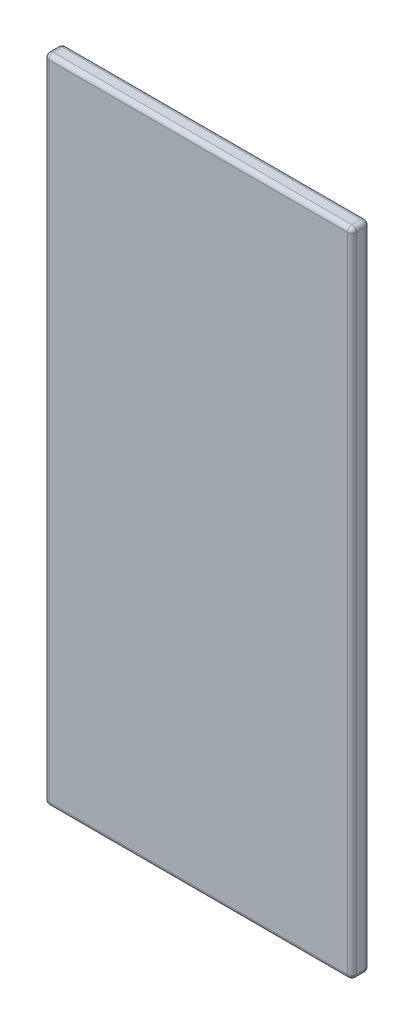
SolidWorks part; units mm, degrees
ref_plane "Front Plane" through (0, 0, 0) normal (0, 0, 1) x (1, 0, 0)
ref_plane "Top Plane" through (0, 0, 0) normal (0, 1, 0) x (1, 0, 0)
ref_plane "Right Plane" through (0, 0, 0) normal (1, 0, 0) x (0, 0, -1)
sketch "Sketch1" plane through (0, 0, 0) normal (0, 0, 1) x (1, 0, 0)
  line L1 (-17.35, -36.75) -> (17.35, -36.75)
  line L2 (-17.35, -36.75) -> (-17.35, 36.75)
  line L3 (-17.35, 36.75) -> (17.35, 36.75)
  line L4 (17.35, -36.75) -> (17.35, 36.75)
  line L5 (-17.35, -36.75) -> (17.35, 36.75) construction
  line L6 (-17.35, 36.75) -> (17.35, -36.75) construction
  point P0 (0, 0)
  dimension "D1" = 34.7
  dimension "D2" = 73.5
extrude "Boss-Extrude1" add sketch "Sketch1" along normal blind 2
fillet "Fillet1" radius 0.5 12 edges at (0, -36.75, 2) (0, -36.75, 0) (-17.35, 0, 2) (-17.35, -36.75, 1) (-17.35, 0, 0) (0, 36.75, 2) (-17.35, 36.75, 1) (0, 36.75, 0) (17.35, -36.75, 1) (17.35, 0, 2) (17.35, 36.75, 1) (17.35, 0, 0)
